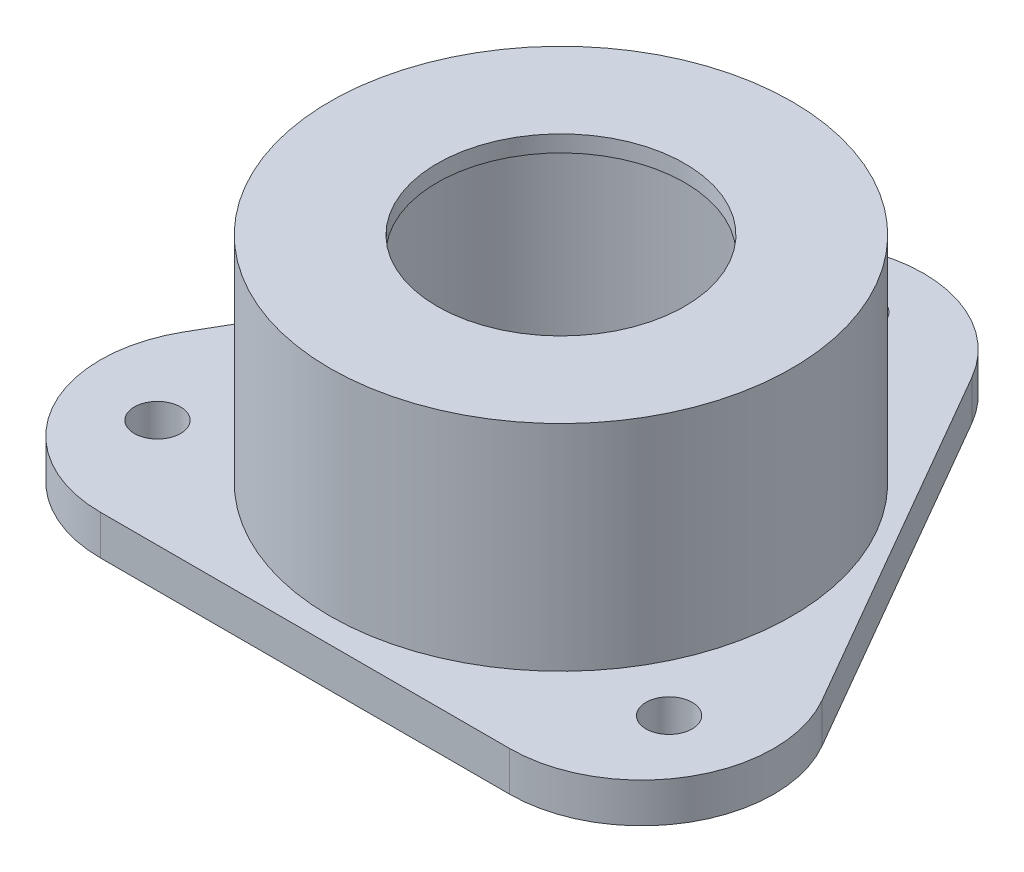
SolidWorks part; units mm, degrees
material "ASTM A36 Steel"
ref_plane "Front Plane" through (0, 0, 0) normal (0, 0, 1) x (1, 0, 0)
ref_plane "Top Plane" through (0, 0, 0) normal (0, 1, 0) x (1, 0, 0)
ref_plane "Right Plane" through (0, 0, 0) normal (1, 0, 0) x (0, 0, -1)
sketch "Sketch1" plane through (0, 0, 0) normal (0, 1, 0) x (1, 0, 0)
  line L0 (66.646, 85.1049) -> (128.644, -22.2787)
  line L1 (94.0029, -82.2787) -> (-29.993, -82.2787)
  line L2 (-64.634, -22.2787) -> (-2.636, 85.1049)
  arc A0 (66.646, 85.1049) -> (-2.636, 85.1049) centre (32.005, 65.1049) ccw
  arc A1 (-29.993, -82.2787) -> (-64.634, -22.2787) centre (-29.993, -42.2787) cw
  arc A2 (128.644, -22.2787) -> (94.0029, -82.2787) centre (94.0029, -42.2787) cw
  point P7 (-99.275, -82.2787)
  point P10 (163.285, -82.2787)
  dimension "D2" = 40
  dimension "D1" = 262.56
extrude "Boss-Extrude1" add sketch "Sketch1" along normal blind 12
sketch "Sketch2" plane through (0, 12, 0) normal (0, 1, 0) x (1, 0, 0)
  circle A0 centre (32.005, -4.7521) radius 37.5
  dimension "D1" = 75
extrude "Cut-Extrude1" cut sketch "Sketch2" against normal blind 22
sketch "Sketch5" plane through (0, 12, 0) normal (0, 1, 0) x (1, 0, 0)
  circle A0 centre (109.505, -49.4967) radius 7
  circle A1 centre (32.005, 84.7372) radius 7
  circle A2 centre (-45.495, -49.4967) radius 7
  dimension "D2" = 14
  dimension "D3" = 14
  dimension "D4" = 14
  dimension "D1" = 155
extrude "Cut-Extrude3" cut sketch "Sketch5" against normal blind 22
sketch "Sketch6" plane through (0, 12, 0) normal (0, 1, 0) x (1, 0, 0)
  circle A0 centre (32.005, -4.7521) radius 70
  dimension "D1" = 140
extrude "Boss-Extrude2" add sketch "Sketch6" along normal blind 65
sketch "Sketch7" plane through (0, 12, 0) normal (0, -1, 0) x (-1, 0, 0)
  circle A0 centre (-32.005, -4.7521) radius 37.5
  dimension "D1" = 75
extrude "Cut-Extrude4" cut sketch "Sketch7" against normal blind 80
sketch "Sketch9" plane through (0, 0, 0) normal (0, -1, 0) x (-1, 0, 0)
  circle A0 centre (-32.005, -4.7521) radius 55
  dimension "D1" = 110
extrude "Cut-Extrude5" cut sketch "Sketch9" against normal blind 72
